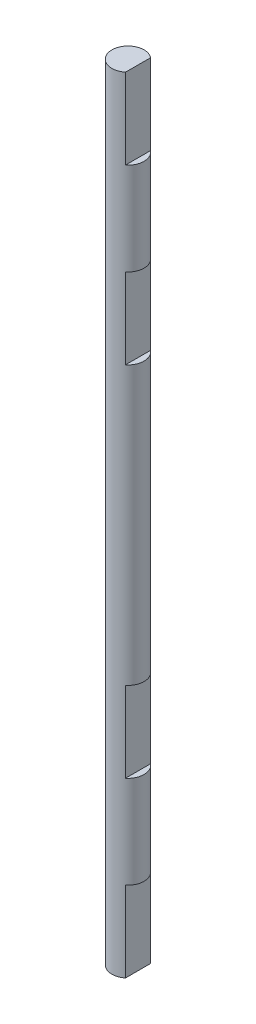
SolidWorks part; units mm, degrees
ref_plane "Front Plane" through (0, 0, 0) normal (0, 0, 1) x (1, 0, 0)
ref_plane "Top Plane" through (0, 0, 0) normal (0, 1, 0) x (1, 0, 0)
ref_plane "Right Plane" through (0, 0, 0) normal (1, 0, 0) x (0, 0, -1)
sketch "Sketch1" plane through (0, 0, 0) normal (0, 1, 0) x (1, 0, 0)
  circle A0 centre (0, 0) radius 4
  dimension "D1" = 8
extrude "Boss-Extrude1" add sketch "Sketch1" along normal blind 195
sketch "Sketch2" plane through (0, 0, 0) normal (0, 0, 1) x (1, 0, 0)
  line L0 (4, 0) -> (4, 195) construction
  line L1 (4, 195) -> (2.5, 195)
  line L2 (4, 195) -> (4, 175)
  line L3 (4, 175) -> (2.5, 175)
  line L4 (2.5, 195) -> (2.5, 175)
  line L5 (4, 195) -> (2.5, 175) construction
  line L6 (4, 175) -> (2.5, 195) construction
  line L7 (4, 152) -> (2.5, 152)
  line L8 (4, 152) -> (4, 132)
  line L9 (4, 132) -> (2.5, 132)
  line L10 (2.5, 152) -> (2.5, 132)
  line L11 (4, 152) -> (2.5, 132) construction
  line L12 (4, 132) -> (2.5, 152) construction
  line L13 (4, 97.5) -> (-4, 97.5) construction
  line L14 (-4, 195) -> (-4, 0) construction
  line L15 (4, 63) -> (2.5, 43) construction
  line L16 (4, 43) -> (2.5, 63) construction
  line L17 (4, 20) -> (2.5, 0) construction
  line L18 (4, 0) -> (2.5, 20) construction
  line L19 (2.5, 43) -> (2.5, 63)
  line L20 (4, 63) -> (2.5, 63)
  line L21 (4, 43) -> (4, 63)
  line L22 (4, 43) -> (2.5, 43)
  line L23 (2.5, 0) -> (2.5, 20)
  line L24 (4, 20) -> (2.5, 20)
  line L25 (4, 0) -> (4, 20)
  line L26 (4, 0) -> (2.5, 0)
  point P4 (3.25, 185)
  point P10 (3.25, 142)
  point P13 (3.25, 175)
  point P26 (3.25, 53)
  point P27 (3.25, 10)
  dimension "D1" = 20
  dimension "D2" = 23
  dimension "D3" = 20
  dimension "D4" = 1.5
extrude "Cut-Extrude1" cut sketch "Sketch2" against normal up to surface and the other way up to surface up to face at (0, 195, 4) other way up to face at (0, 195, 4)
